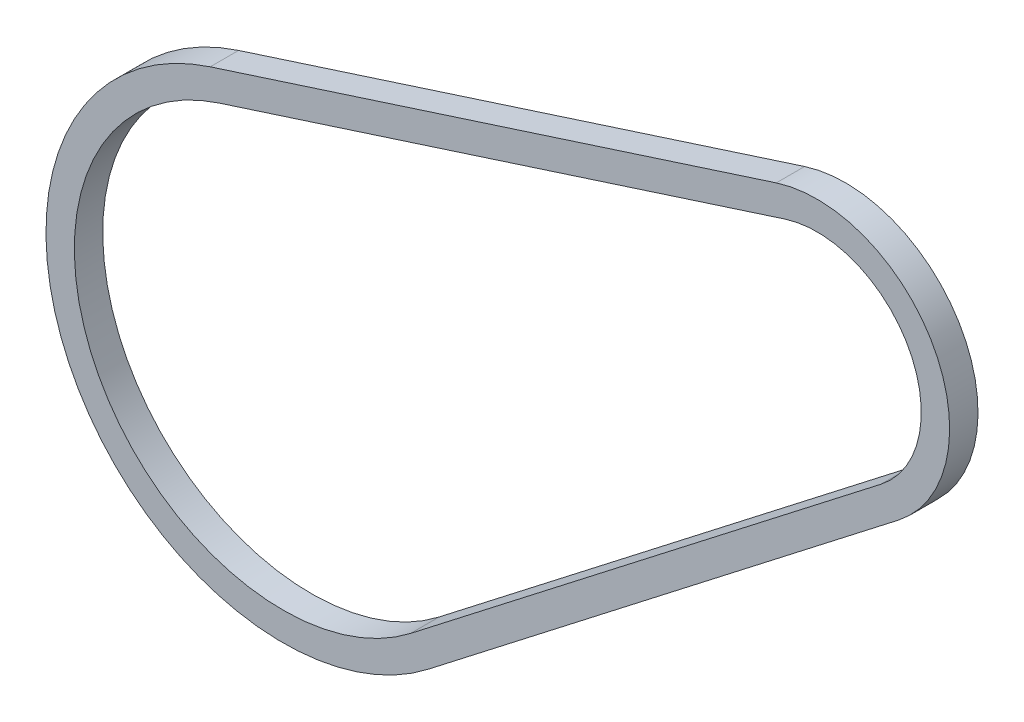
SolidWorks part; units mm, degrees
material "Caucho"
ref_plane "Alzado" through (0, 0, 0) normal (0, 0, 1) x (1, 0, 0)
ref_plane "Planta" through (0, 0, 0) normal (0, 1, 0) x (1, 0, 0)
ref_plane "Vista lateral" through (0, 0, 0) normal (1, 0, 0) x (0, 0, -1)
sketch "Croquis2" plane through (0, 0, 0) normal (0, 0, 1) x (1, 0, 0)
  line L0 (0, 0) -> (1, 0) construction
  line L1 (0, 0) -> (0, 1) construction
  line L2 (-22.5548, 69.9538) -> (176.9024, 134.2635)
  line L3 (210.6854, 70.2339) -> (45.0113, -58.1054)
  arc A0 (45.0113, -58.1054) -> (-22.5548, 69.9538) centre (0, 0) cw
  arc A1 (176.9024, 134.2635) -> (210.6854, 70.2339) centre (188.1798, 99.2866) cw
extrude "Extruir-Lámina1" add sketch "Croquis2" along normal mid plane 10 thin thin type one direction wall 10
